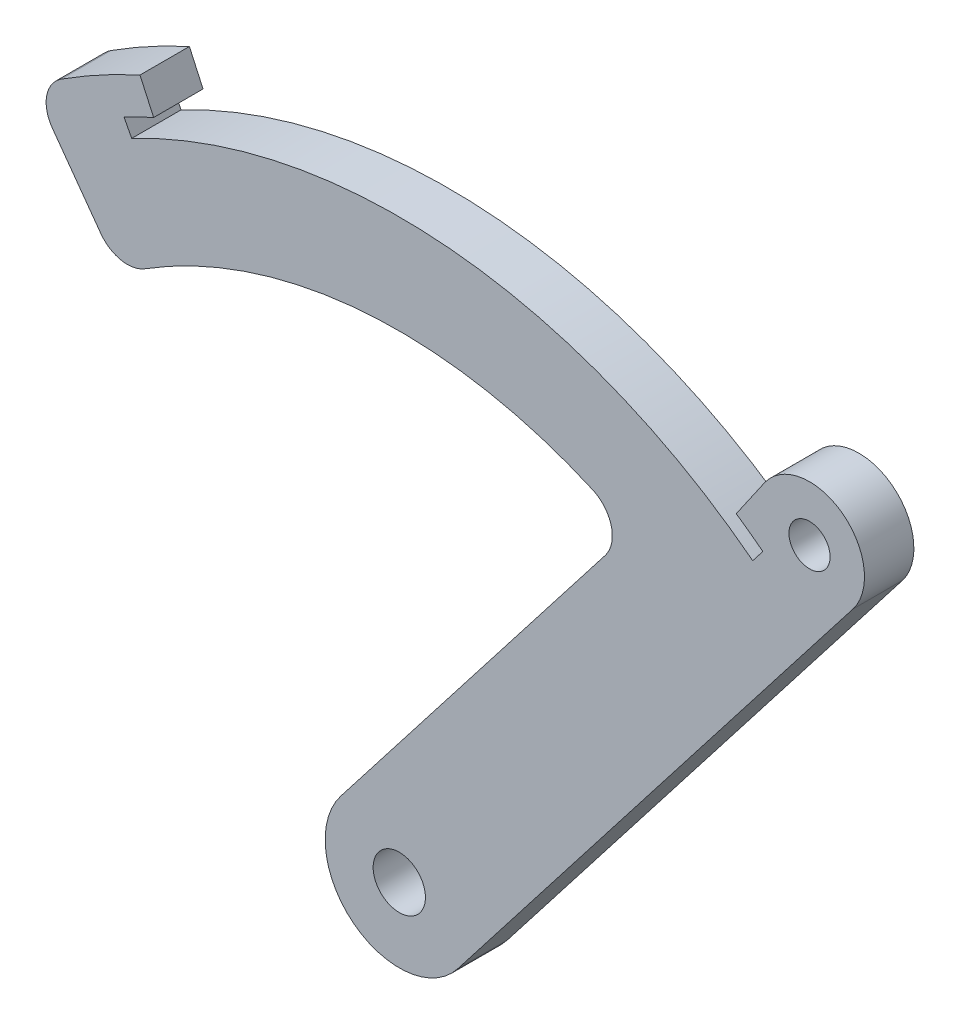
SolidWorks part; units mm, degrees
ref_plane "Front Plane" through (0, 0, 0) normal (0, 0, 1) x (1, 0, 0)
ref_plane "Top Plane" through (0, 0, 0) normal (0, 1, 0) x (1, 0, 0)
ref_plane "Right Plane" through (0, 0, 0) normal (1, 0, 0) x (0, 0, -1)
sketch "Sketch1" plane through (0, 0, 0) normal (0, 0, 1) x (1, 0, 0)
  line L1 (-14.9542, 193.4883) -> (-38.9453, 162.582)
  line L3 (-46.0547, 168.1007) -> (-29.9855, 188.8017)
  line L4 (-58.7481, 196.3413) -> (-59.2123, 197.227)
  line L5 (-21.0384, 192.9891) -> (-20.4252, 193.779)
  line L7 (-22.0385, 194.961) -> (-20.3334, 197.4293)
  line L9 (-57.4158, 198.1059) -> (-58.2444, 199.9262)
  line L11 (-63.5634, 194.4675) -> (-60.6282, 190.4086)
  arc A0 (-21.0384, 192.9891) -> (-58.7481, 196.3413) centre (-42.5, 165.3413) ccw construction
  arc A1 (-21.0384, 192.9891) -> (-58.7481, 196.3413) centre (-42.5, 165.3413) ccw construction
  circle A2 centre (-42.5, 165.3413) radius 1.5875
  arc A3 (-30.7554, 191.8567) -> (-57.9425, 189.8878) centre (-42.5, 165.3413) ccw
  arc A4 (-58.7481, 196.3413) -> (-21.0384, 192.9891) centre (-42.5, 165.3413) cw
  arc A5 (-59.2123, 197.227) -> (-57.4158, 198.1059) centre (-42.5, 165.3413) cw
  arc A6 (-63.0229, 197.3227) -> (-58.2444, 199.9262) centre (-42.5, 165.3413) cw
  arc A7 (-20.4252, 193.779) -> (-22.0385, 194.961) centre (-42.5, 165.3413) ccw
  arc A8 (-63.5634, 194.4675) -> (-63.0229, 197.3227) centre (-61.9428, 195.6395) cw
  arc A9 (-14.9542, 193.4883) -> (-20.3334, 197.4293) centre (-17.5891, 195.5335) ccw
  circle A10 centre (-17.5891, 195.5335) radius 1.25
  arc A11 (-29.9855, 188.8017) -> (-30.7554, 191.8567) centre (-31.5654, 190.028) ccw
  arc A12 (-60.6282, 190.4086) -> (-57.9425, 189.8878) centre (-59.0075, 191.5806) ccw
  arc A13 (-38.9453, 162.582) -> (-46.0547, 168.1007) centre (-42.5, 165.3413) cw
  dimension "D1" = 2
  dimension "D6" = 3.175
  dimension "D9" = 6
  dimension "D12" = 2.5
  dimension "D13" = 38
  dimension "D14" = 2
  dimension "D2" = 1
  dimension "D4" = 4.5
  dimension "D8" = 3
  dimension "D10" = 2
  dimension "D11" = 5
extrude "Boss-Extrude1" add sketch "Sketch1" against normal up to vertex (3 mm away)
ref_point "Point1"
